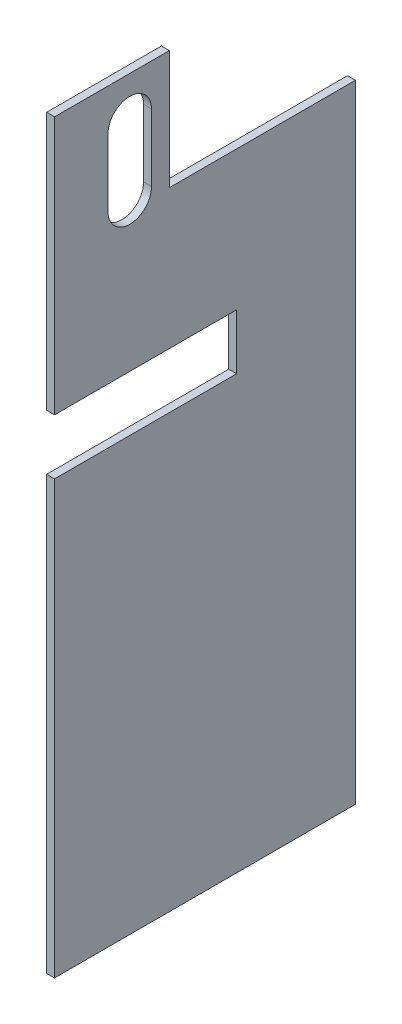
SolidWorks part; units mm, degrees
material "Teak"
ref_plane "Front Plane" through (0, 0, 0) normal (0, 0, 1) x (1, 0, 0)
ref_plane "Top Plane" through (0, 0, 0) normal (0, 1, 0) x (1, 0, 0)
ref_plane "Right Plane" through (0, 0, 0) normal (1, 0, 0) x (0, 0, -1)
sketch "Sketch1" plane through (0, 0, 0) normal (1, 0, 0) x (0, 0, -1)
  line L0 (0, 0) -> (0, 546)
  line L1 (0, 942) -> (145, 942)
  line L2 (145, 942) -> (145, 792)
  line L3 (145, 792) -> (380, 792)
  line L4 (380, 792) -> (380, 0)
  line L5 (380, 0) -> (0, 0)
  line L6 (95, 889.5) -> (95, 804.5) construction
  line L7 (122.5, 889.5) -> (122.5, 804.5)
  line L8 (67.5, 889.5) -> (67.5, 804.5)
  line L9 (0, 616) -> (0, 942)
  line L10 (0, 616) -> (230, 616)
  line L12 (0, 546) -> (230, 546)
  line L13 (230, 616) -> (230, 546)
  arc A0 (122.5, 889.5) -> (67.5, 889.5) centre (95, 889.5) ccw
  arc A1 (67.5, 804.5) -> (122.5, 804.5) centre (95, 804.5) ccw
  point P9 (95, 847)
  point P18 (95, 917)
  dimension "D1" = 942
  dimension "D2" = 145
  dimension "D3" = 792
  dimension "D4" = 380
  dimension "D5" = 230
  dimension "D6" = 70
  dimension "D7" = 546
  dimension "D8" = 55
  dimension "D9" = 85
  dimension "D10" = 25
  dimension "D11" = 95
extrude "Boss-Extrude1" add sketch "Sketch1" along normal blind 10 contours L10 L13 L12 L0 L5 L4 L3 L2 L1 L9 A1 L8 A0 L7
